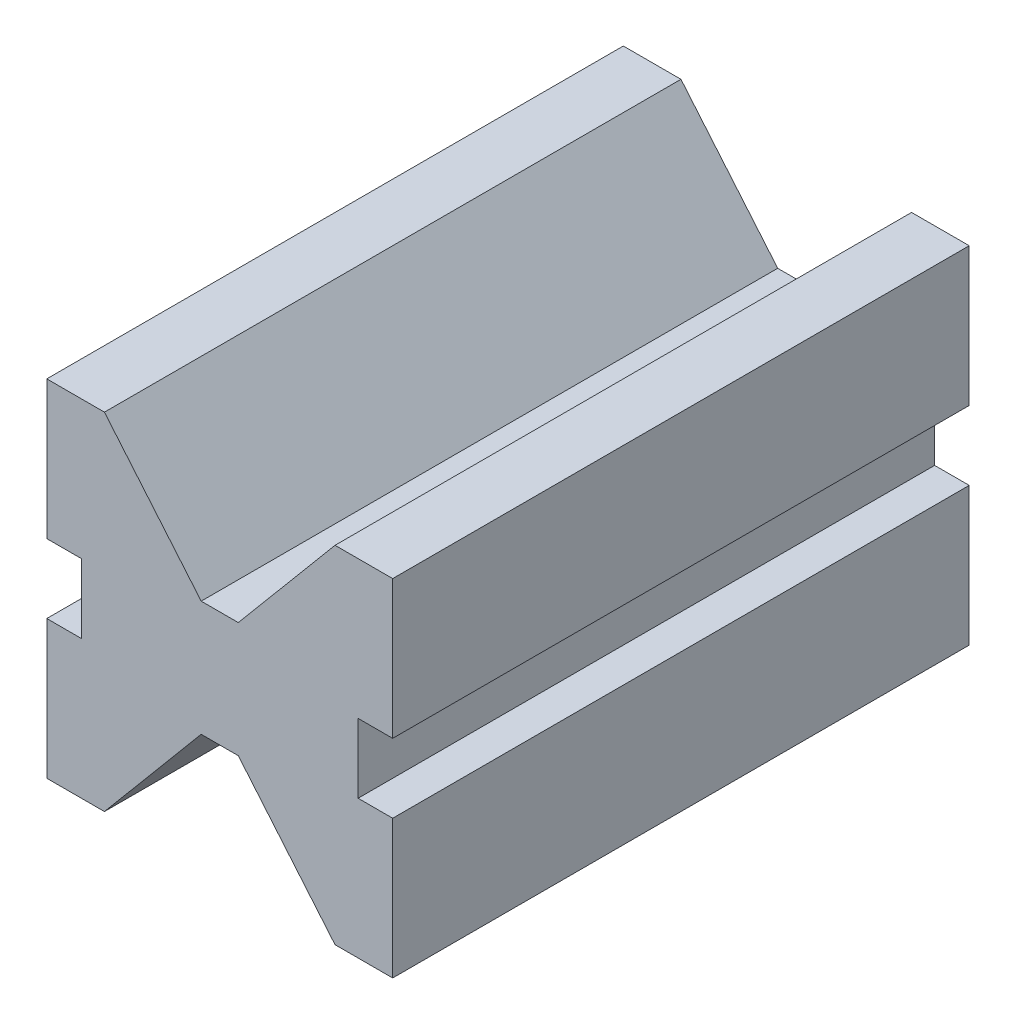
SolidWorks part; units mm, degrees
ref_plane "정면" through (0, 0, 0) normal (0, 0, 1) x (1, 0, 0)
ref_plane "윗면" through (0, 0, 0) normal (0, 1, 0) x (1, 0, 0)
ref_plane "우측면" through (0, 0, 0) normal (1, 0, 0) x (0, 0, -1)
sketch "스케치1" plane through (0, 0, 0) normal (0, 0, 1) x (1, 0, 0)
  line L1 (-30, 30) -> (30, 30)
  line L2 (-30, 30) -> (-30, -30)
  line L3 (-30, -30) -> (30, -30)
  line L4 (30, 30) -> (30, -30)
  line L5 (0, -30) -> (0, 30) construction
  line L6 (-30, 0) -> (30, 0) construction
  point P0 (0, 0)
  dimension "D1" = 60
extrude "보스-돌출1" add sketch "스케치1" along normal blind 100
sketch "스케치2" plane through (0, 0, 100) normal (0, 0, 1) x (1, 0, 0)
  line L0 (0, 30) -> (0, -30) construction
  line L1 (30, 30) -> (-30, 30) construction
  line L2 (-30, -30) -> (30, -30) construction
  line L4 (-20, -30) -> (-3.218, -10)
  line L5 (-3.218, -10) -> (3.218, -10)
  line L6 (20, -30) -> (3.218, -10)
  point P10 (0, -10)
  dimension "D1" = 40
  dimension "D2" = 50
  dimension "D3" = 20
extrude "컷-돌출2" cut sketch "스케치2" along direction (0, 0, 1) on the side against the normal blind 100 and the other way through all flip side to cut
mirror "대칭 복사1" about plane through (0, 0, 0) normal (0, 1, 0) of "컷-돌출2"
sketch "스케치5" plane through (0, 0, 100) normal (0, 0, 1) x (1, 0, 0)
  line L0 (30, -30) -> (30, 30) construction
  line L1 (24, 6) -> (36, 6)
  line L2 (24, 6) -> (24, -6)
  line L3 (24, -6) -> (36, -6)
  line L4 (36, 6) -> (36, -6)
  line L5 (30, -6) -> (30, 6) construction
  line L6 (24, 0) -> (36, 0) construction
  point P0 (30, 0)
  dimension "D1" = 24
  dimension "D2" = 6
extrude "컷-돌출3" cut sketch "스케치5" against normal through all
mirror "대칭 복사2" about plane through (0, 0, 0) normal (1, 0, 0) of "컷-돌출3"
